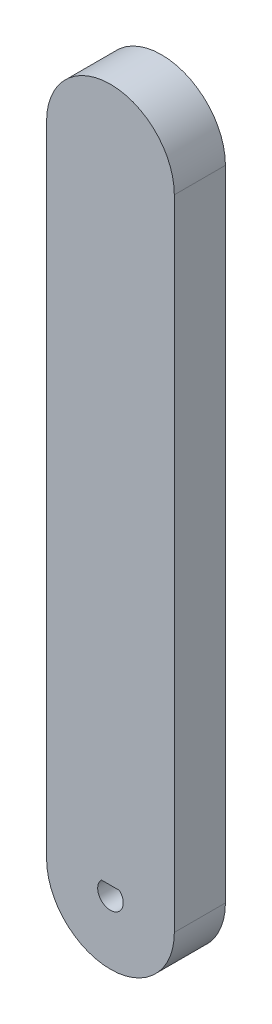
SolidWorks part; units mm, degrees
ref_plane "Alzado" through (0, 0, 0) normal (0, 0, 1) x (1, 0, 0)
ref_plane "Planta" through (0, 0, 0) normal (0, 1, 0) x (1, 0, 0)
ref_plane "Vista lateral" through (0, 0, 0) normal (1, 0, 0) x (0, 0, -1)
sketch "Croquis1" plane through (0, 0, 0) normal (0, 0, 1) x (1, 0, 0)
  line L0 (-1.4283, 1.4) -> (1.4283, 1.4)
  arc A0 (-1.4283, 1.4) -> (1.4283, 1.4) centre (0, 0) ccw
sketch "Croquis3" plane through (0, 0, 0) normal (0, 0, 1) x (1, 0, 0)
  line L0 (-1.4283, 1.4) -> (1.4283, 1.4)
  line L1 (0, 0) -> (0, 1.4)
  line L2 (-10, 100) -> (-10, 0)
  line L3 (10, 100) -> (10, 0)
  arc A0 (-1.4283, 1.4) -> (1.4283, 1.4) centre (0, 0) ccw
  arc A1 (-10, 0) -> (10, 0) centre (0, 0) ccw
  arc A2 (10, 100) -> (-10, 100) centre (0, 100) ccw
  dimension "D1" = 20
  dimension "D3" = 20
  dimension "D2" = 100
extrude "Saliente-Extruir1" add sketch "Croquis3" along normal blind 8 contours L3 A2 L2 A1 A0 L0
